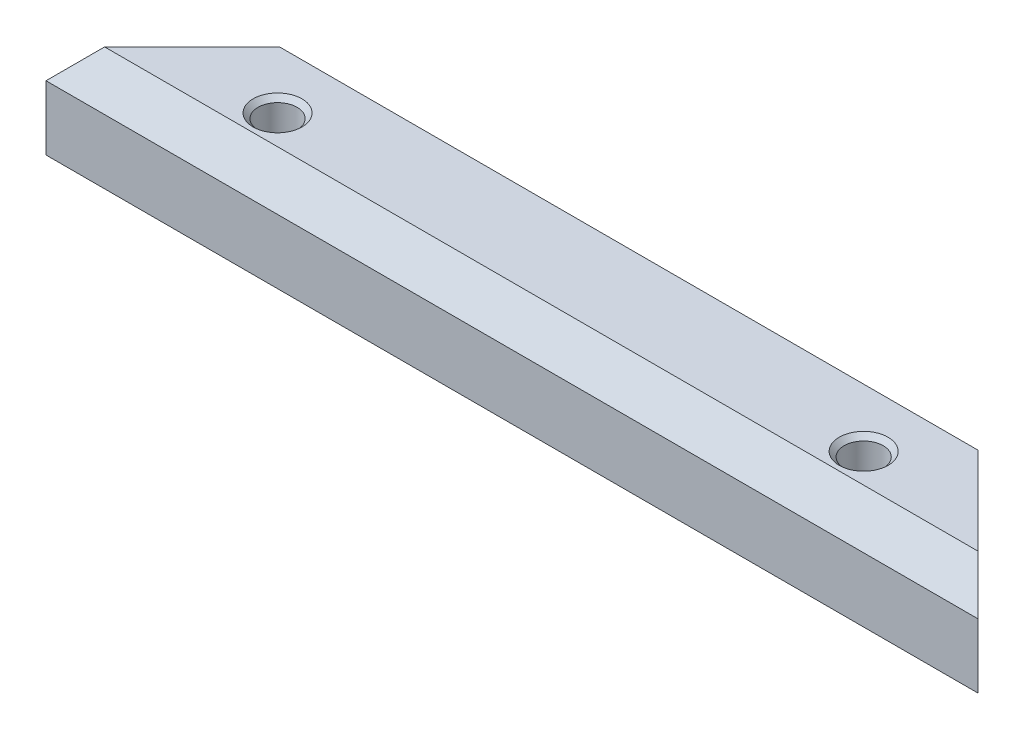
SolidWorks part; units mm, degrees
ref_plane "Front Plane" through (0, 0, 0) normal (0, 0, 1) x (1, 0, 0)
ref_plane "Top Plane" through (0, 0, 0) normal (0, 1, 0) x (1, 0, 0)
ref_plane "Right Plane" through (0, 0, 0) normal (1, 0, 0) x (0, 0, -1)
sketch "Sketch1" plane through (0, 0, 0) normal (0, 1, 0) x (1, 0, 0)
  line L0 (-95.41, 0) -> (95.41, 0)
  line L1 (-69.5, 25.91) -> (69.5, 25.91)
  line L2 (-95.41, 0) -> (-69.5, 25.91)
  line L3 (69.5, 25.91) -> (95.41, 0)
  point P4 (0, 0)
  point P8 (0, 25.91)
  dimension "D1" = 139
  dimension "D2" = 45
  dimension "D3" = 45
  dimension "D4" = 25.91
extrude "Boss-Extrude1" add sketch "Sketch1" along normal blind 3
sketch "Sketch4" plane through (0, 3, 0) normal (0, 1, 0) x (1, 0, 0)
  line L0 (0, -1000) -> (0, 49000) construction
  line L1 (-95.41, 0) -> (95.41, 0) construction
  circle A0 centre (0, 133.2) radius 120 construction
  point P7 (0, 0)
  dimension "D2" = 240
  dimension "D1" = 133.2
sketch "Sketch5" plane through (0, 3, 0) normal (0, 1, 0) x (1, 0, 0)
  line L0 (69.5, 25.91) -> (-69.5, 25.91) construction
  line L1 (-64.4969, 25.91) -> (-69.5, 25.91)
  line L2 (-69.5, 25.91) -> (-95.41, 0)
  line L3 (-95.41, 0) -> (95.41, 0)
  line L4 (95.41, 0) -> (69.5, 25.91)
  line L5 (69.5, 25.91) -> (64.4969, 25.91)
  arc A0 (-45.5273, 22.1718) -> (45.5273, 22.1718) centre (0, 133.2) ccw
  circle A1 centre (0, 133.2) radius 120 construction
  arc A2 (45.5273, 22.1718) -> (64.4969, 25.91) centre (64.4969, -24.09) cw
  arc A3 (-45.5273, 22.1718) -> (-64.4969, 25.91) centre (-64.4969, -24.09) ccw
  point P18 (53.7481, 25.91)
  point P21 (-53.7481, 25.91)
  dimension "D1" = 50
extrude "Boss-Extrude2" add sketch "Sketch5" along normal blind 12
sketch "Sketch7" plane through (0, 15, 0) normal (0, 1, 0) x (1, 0, 0)
  line L0 (-95.41, 0) -> (-69.5, 25.91)
  line L1 (-69.5, 25.91) -> (69.5, 25.91)
  line L2 (69.5, 25.91) -> (95.41, 0)
  line L3 (95.41, 0) -> (-95.41, 0)
extrude "Boss-Extrude3" add sketch "Sketch7" along normal blind 4.17
sketch "Sketch3" plane through (0, 3, 0) normal (0, 1, 0) x (1, 0, 0)
  line L0 (0, -1000) -> (0, 49000) construction
  line L1 (-988.1148, 12) -> (49011.8852, 12) construction
  line L3 (-95.41, 0) -> (95.41, 0) construction
  circle A0 centre (-60, 12) radius 2
  circle A3 centre (60, 12) radius 2
  point P14 (0, -36.5425)
  dimension "D1" = 4
  dimension "D2" = 60
  dimension "D3" = 12
extrude "Cut-Extrude1" cut sketch "Sketch3" against normal through all both and the other way through all
chamfer "Chamfer1" distance 6 angle 45 1 edges at (0, 19.17, 0)
sketch "Sketch8" plane through (0, 19.17, 0) normal (0, 1, 0) x (1, 0, 0)
  circle A0 centre (-60, 12) radius 4
  circle A1 centre (60, 12) radius 4
  circle A2 centre (60, 12) radius 2 construction
  dimension "D1" = 8
  dimension "D2" = 8
extrude "Cut-Extrude2" cut sketch "Sketch8" against normal offset from surface (7.17 mm away) 12 up to face at (-60, 0, -10)
chamfer "Chamfer2" distance 1 angle 45 2 edges at (-60, 19.17, -8) (60, 19.17, -8)
sketch "Sketch9" plane through (0, 0, 0) normal (0, -1, 0) x (-1, 0, 0)
  circle A0 centre (60, 12) radius 4
  circle A1 centre (30, 12) radius 4
  circle A2 centre (-30, 12) radius 4
  circle A3 centre (-60, 12) radius 4
  dimension "D1" = 8
  dimension "D2" = 30
  dimension "D3" = 60
extrude "Cut-Extrude4" cut sketch "Sketch9" against normal blind 5
chamfer "Chamfer3" distance 2 angle 45 1 edges at (0, 19.17, -25.91)
